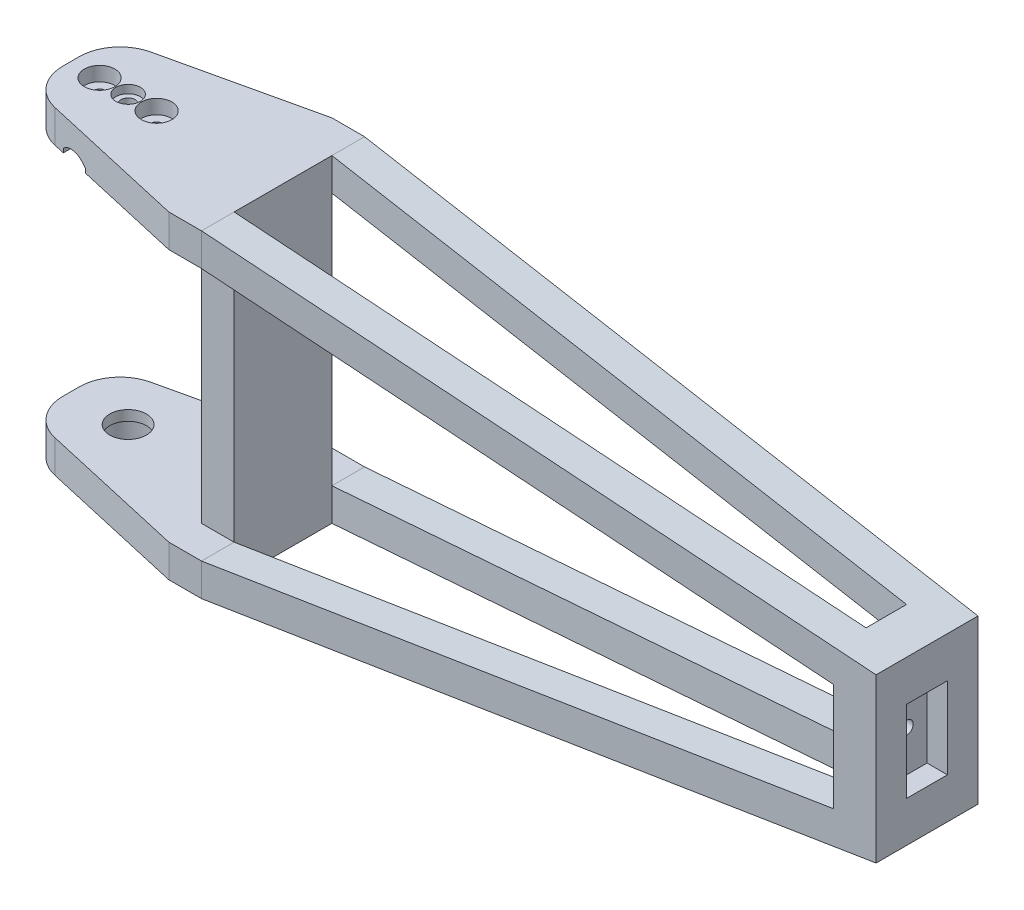
SolidWorks part; units mm, degrees
material "ABS"
ref_plane "Płaszczyzna przednia" through (0, 0, 0) normal (0, 0, 1) x (1, 0, 0)
ref_plane "Płaszczyzna górna" through (0, 0, 0) normal (0, 1, 0) x (1, 0, 0)
ref_plane "Płaszczyzna prawa" through (0, 0, 0) normal (1, 0, 0) x (0, 0, -1)
sketch "Szkic1" plane through (0, 0, 0) normal (0, 1, 0) x (1, 0, 0)
  line L0 (-14, -10) -> (30, -20)
  line L2 (-14, 10) -> (-14, -10)
  line L5 (-55, 0) -> (55, 0) construction
  line L6 (0, 0) -> (12.6728, 0) construction
  line L7 (-14, 10) -> (30, 20)
  line L10 (30, 20) -> (38, 20)
  line L12 (30, -20) -> (38, -20)
  line L13 (38, 20) -> (38, -20)
  circle A0 centre (0, 0) radius 4.5
  point P11 (30, 0)
  dimension "D1" = 9
  dimension "D4" = 14
  dimension "D2" = 20
  dimension "D3" = 30
  dimension "D5" = 8
  dimension "D6" = 40
extrude "Dodanie-wyciągnięcie1" add sketch "Szkic1" along normal blind 8
sketch "Szkic4" plane through (0, 8, 0) normal (0, 1, 0) x (1, 0, 0)
  line L7 (30, 20) -> (38, 20)
  line L8 (30, 20) -> (30, -20)
  line L9 (30, -20) -> (38, -20)
  line L10 (38, 20) -> (38, -20)
sketch "Szkic23" plane through (0, 0, 0) normal (0, -1, 0) x (1, 0, 0)
  circle A0 centre (0, 0) radius 6.5
  dimension "D1" = 13
extrude "Wytnij-wyciągnięcie11" cut sketch "Szkic23" against normal offset from surface (5.5 mm away) 2.5 up to face at (0, 8, 4.5)
extrude "Dodanie-wyciągnięcie2" add sketch "Szkic4" along normal blind 62.15
sketch "Szkic5" plane through (0, 70.15, 0) normal (0, 1, 0) x (1, 0, 0)
  line L6 (38, 20) -> (30, 20)
  line L7 (38, 20) -> (30, 20) construction
  line L8 (30, 20) -> (30, -20) construction
  line L9 (30, 20) -> (-14, 10)
  line L10 (-14, 10) -> (-14, -10)
  line L11 (-14, -10) -> (30, -20)
  line L12 (30, -20) -> (38, -20)
  line L13 (38, -20) -> (38, 20)
  line L14 (-14, 10) -> (30, 20) construction
  line L15 (-14, -10) -> (30, -20) construction
  line L16 (-14, 10) -> (-14, -10) construction
extrude "Dodanie-wyciągnięcie3" add sketch "Szkic5" along normal blind 8
sketch "Szkic6" plane through (0, 78.15, 0) normal (0, 1, 0) x (1, 0, 0)
  line L2 (-55, 0) -> (55, 0) construction
  line L3 (0, -55) -> (0, 55) construction
  circle A2 centre (-7, 0) radius 1.6
  circle A3 centre (7, 0) radius 1.6
  point P11 (0.0979, -0.4093)
  dimension "D1" = 3.2
  dimension "D2" = 7
extrude "Wytnij-wyciągnięcie3" cut sketch "Szkic6" against normal up to next
sketch "Szkic7" plane through (0, 78.15, 0) normal (0, 1, 0) x (1, 0, 0)
  circle A0 centre (7, 0) radius 3.75
  circle A1 centre (-7, 0) radius 3.75
  dimension "D1" = 7.5
  dimension "D2" = 7.5
extrude "Wytnij-wyciągnięcie4" cut sketch "Szkic7" against normal blind 3.5
ref_plane "Płaszczyzna1" through (0, 0, 0) normal (1, 0, 0) x (0, 0, -1)
sketch "Szkic9" plane through (-14, 0, 0) normal (0, 0, 1) x (1, 0, 0)
  line L0 (10.5, 70.15) -> (17.5, 70.15)
  line L1 (10.5, 70.15) -> (10.5, 71.15)
  line L2 (17.5, 70.15) -> (17.5, 71.15)
  line L5 (14, -55) -> (14, 55) construction
  line L6 (14, 70.0564) -> (14, 58.6294) construction
  line L8 (0, 70.15) -> (44, 70.15) construction
  arc A0 (17.5, 71.15) -> (10.5, 71.15) centre (14, 67.5793) ccw
  dimension "D3" = 5
  dimension "D4" = 3.5
  dimension "D1" = 1
  dimension "D2" = 3.5
extrude "Wytnij-wyciągnięcie5" cut sketch "Szkic9" against normal up to next and the other way up to next
sketch "Szkic10" plane through (0, 78.15, 0) normal (0, 1, 0) x (1, 0, 0)
  circle A0 centre (0, 0) radius 3
  dimension "D1" = 6
extrude "Wytnij-wyciągnięcie6" cut sketch "Szkic10" against normal blind 2
sketch "Szkic14" plane through (30, 0, 0) normal (-1, 0, 0) x (0, 0, 1)
  line L0 (-20, 70.15) -> (20, 70.15) construction
  line L1 (-12, 70.15) -> (12, 70.15)
  line L2 (-12, 70.15) -> (-12, 8)
  line L3 (-12, 8) -> (12, 8)
  line L4 (12, 70.15) -> (12, 8)
  line L6 (-12, 70.15) -> (-20, 70.15)
  line L7 (-20, 8) -> (20, 8) construction
  line L8 (-20, 78.15) -> (-20, 70.15) construction
  line L9 (-12, 70.15) -> (-12, 8)
  line L10 (-12, 8) -> (-20, 8)
  line L11 (-20, 70.15) -> (-20, 8)
  line L12 (12, 70.15) -> (20, 70.15)
  line L13 (12, 70.15) -> (12, 8)
  line L14 (12, 8) -> (20, 8)
  line L15 (20, 70.15) -> (20, 8)
  dimension "D1" = 8
  dimension "D2" = 8
extrude "Wytnij-wyciągnięcie7" cut sketch "Szkic14" against normal up to next contours L13 L12 L15 L14 | L9 L6 L11 L10
sketch "Szkic17" plane through (0, 0, 0) normal (0, -1, 0) x (1, 0, 0)
  line L0 (28.6, 0) -> (-28.6, 0) construction
  line L1 (38, 20) -> (196, 12.5)
  line L2 (38, -20) -> (196, -12.5)
  line L3 (196, 12.5) -> (196, -12.5)
  line L4 (38, 20) -> (38, 11.991)
  line L5 (186, -4.9657) -> (186, 4.9657)
  line L6 (186, 4.9657) -> (38, 11.991)
  line L7 (30, -20) -> (38, -20) construction
  line L8 (186, -4.9657) -> (38, -11.991)
  line L9 (38, -20) -> (38, 20) construction
  line L10 (38, -11.991) -> (38, -20)
  line L11 (38, -11.991) -> (38.3793, -19.982) construction
  point P7 (196, 0)
  point P16 (34.0042, 34.8729)
  dimension "D1" = 10
  dimension "D2" = 158
  dimension "D3" = 25
  dimension "D4" = 8
extrude "Dodanie-wyciągnięcie5" add sketch "Szkic17" against normal through all
sketch "Szkic18" plane through (0, 0, -20) normal (0, 0, -1) x (-1, 0, 0)
  line L0 (-30, 39.075) -> (-196, 39.075) construction
  line L1 (-30, 70.15) -> (-30, 8) construction
  line L3 (-196, 59.075) -> (-196, 78.15)
  line L6 (-38, 78.15) -> (-196, 59.075)
  line L11 (-196, 78.15) -> (-196, 0) construction
  line L12 (-196, 59.075) -> (-196, 19.075)
  line L13 (-196, 19.075) -> (-38, 0)
  line L19 (-38, 0) -> (-38, 8)
  line L20 (-196, 78.15) -> (-38, 78.15)
  line L21 (-38, 8) -> (-186, 25.8677)
  line L22 (-186, 25.8677) -> (-186, 52.2823)
  line L23 (-186, 52.2823) -> (-38, 70.15)
  line L24 (-38, 70.15) -> (-38, 8)
  line L25 (-38, 0) -> (-196, 0)
  line L26 (-196, 0) -> (-196, 19.075)
  dimension "D1" = 40
  dimension "D2" = 10
extrude "Wytnij-wyciągnięcie9" cut sketch "Szkic18" against normal through all and the other way through all contours L26 L25 L13 | L3 L20 L6 | L21 L22 L23 L24
sketch "Szkic20" plane through (196, 0, 0) normal (1, 0, 0) x (0, 0, -1)
  line L13 (-12.5, 39.075) -> (12.5, 39.075) construction
  line L14 (-12.5, 59.075) -> (-12.5, 19.075) construction
  line L16 (12.5, 59.075) -> (12.5, 19.075) construction
  line L18 (0, 59.075) -> (0, 19.0008) construction
  line L19 (-12.5, 59.075) -> (12.5, 59.075) construction
  line L20 (0, 42.9826) -> (0, -42.9826) construction
  line L21 (-5, 49.075) -> (5, 49.075)
  line L22 (-5, 49.075) -> (-5, 29.075)
  line L23 (-5, 29.075) -> (5, 29.075)
  line L24 (5, 49.075) -> (5, 29.075)
  dimension "D1" = 20
  dimension "D2" = 10
extrude "Wytnij-wyciągnięcie10" cut sketch "Szkic20" against normal blind 5
fillet "Zaokrąglenie1" radius 10 4 edges at (-14, 74.15, 10) (-14, 4, 10) (-14, 4, -10) (-14, 74.15, -10)
sketch "Szkic24" plane through (0, 76.15, 0) normal (0, 1, 0) x (1, 0, 0)
  circle A0 centre (0, 0) radius 1.75
  dimension "D1" = 3.5
extrude "Wytnij-wyciągnięcie12" cut sketch "Szkic24" against normal up to next
sketch "Szkic25" plane through (191, 0, 0) normal (1, 0, 0) x (0, 0, -1)
  line L0 (5, 49.075) -> (-5, 29.075) construction
  line L1 (-5, 49.075) -> (5, 29.075) construction
  circle A0 centre (0, 39.075) radius 1.6
  dimension "D1" = 3.2
extrude "Wytnij-wyciągnięcie13" cut sketch "Szkic25" against normal up to next
